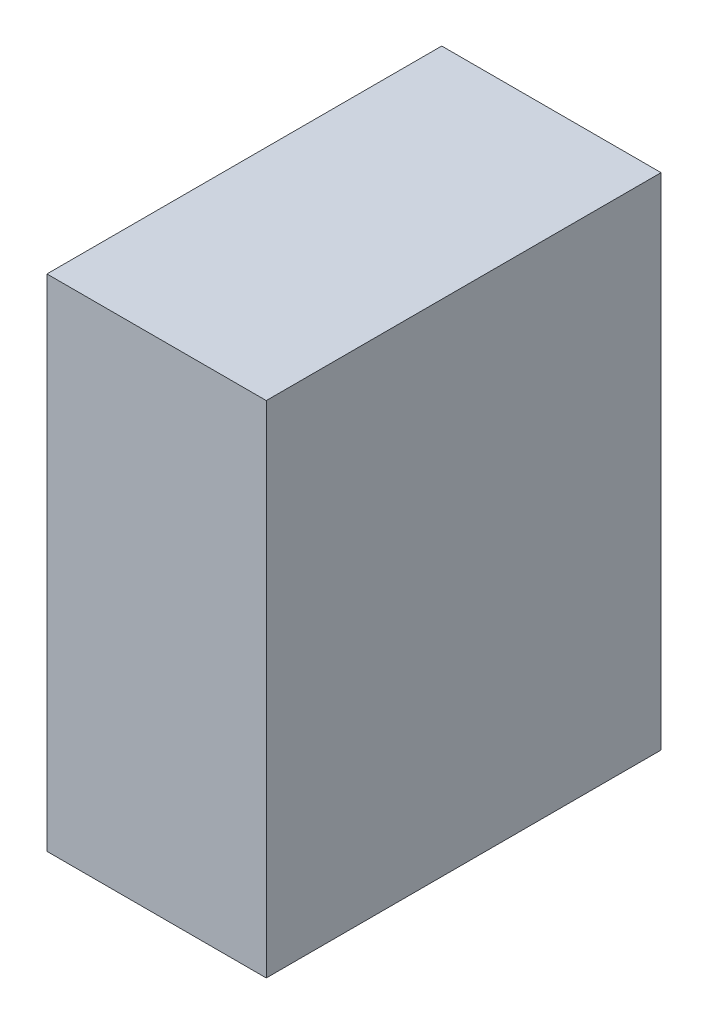
SolidWorks part; units mm, degrees
material "Porcelana cerâmica"
ref_plane "Plano frontal" through (0, 0, 0) normal (0, 0, 1) x (1, 0, 0)
ref_plane "Plano superior" through (0, 0, 0) normal (0, 1, 0) x (1, 0, 0)
ref_plane "Plano direito" through (0, 0, 0) normal (1, 0, 0) x (0, 0, -1)
sketch "Esboço1" plane through (0, 0, 0) normal (0, 0, 1) x (1, 0, 0)
  line L1 (0, 0) -> (50, 0)
  line L2 (0, 0) -> (0, 114)
  line L3 (0, 114) -> (50, 114)
  line L4 (50, 0) -> (50, 114)
  dimension "D1" = 114
  dimension "D2" = 50
extrude "Ressalto-extrusão1" add sketch "Esboço1" along normal blind 90
